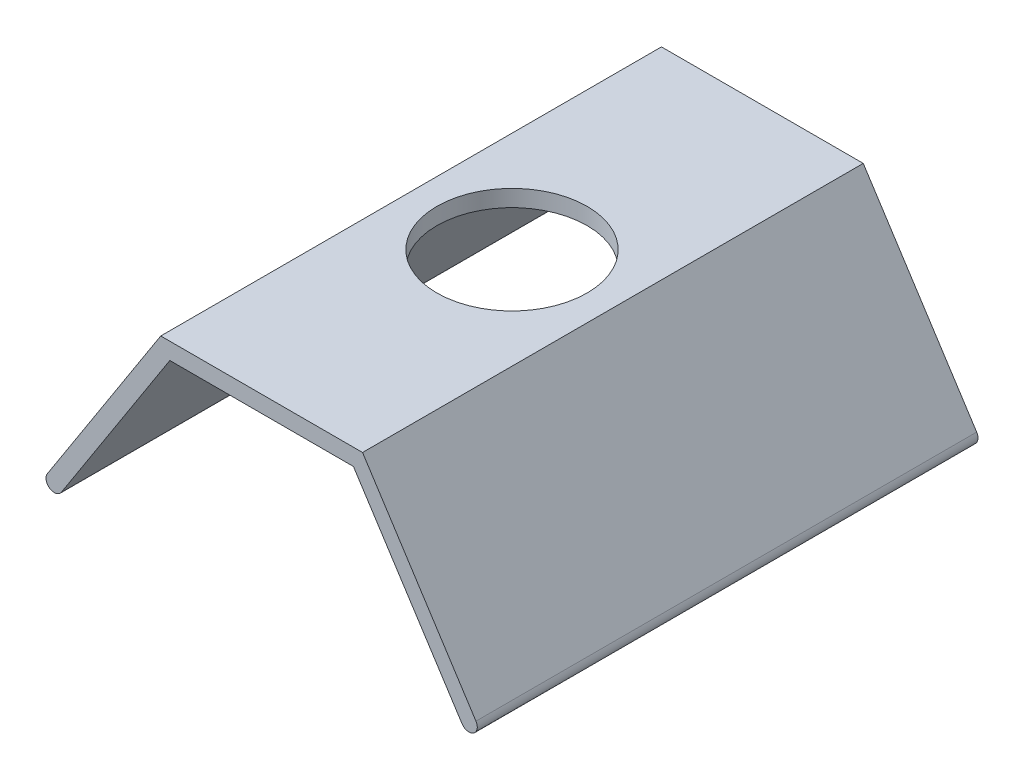
SolidWorks part; units mm, degrees
ref_plane "Front Plane" through (0, 0, 0) normal (0, 0, 1) x (1, 0, 0)
ref_plane "Top Plane" through (0, 0, 0) normal (0, 1, 0) x (1, 0, 0)
ref_plane "Right Plane" through (0, 0, 0) normal (1, 0, 0) x (0, 0, -1)
sketch "Sketch1" plane through (0, 0, 0) normal (0, 0, 1) x (1, 0, 0)
  line L0 (-2.75, 0) -> (2.75, 0)
  line L1 (2.75, 0) -> (6, -5.0436)
  line L2 (-2.75, 0) -> (-6, -5.0436)
  line L3 (3.0226, 0.5) -> (6.4203, -4.7727)
  line L4 (-3.0226, 0.5) -> (3.0226, 0.5)
  line L5 (-3.0226, 0.5) -> (-6.4203, -4.7727)
  arc A0 (6, -5.0436) -> (6.4203, -4.7727) centre (6.2101, -4.9081) ccw
  arc A1 (-6, -5.0436) -> (-6.4203, -4.7727) centre (-6.2101, -4.9081) cw
  point P4 (0, 0)
  dimension "D1" = 12
  dimension "D2" = 5.5
  dimension "D3" = 6
  dimension "D4" = 0.5
extrude "Boss-Extrude1" add sketch "Sketch1" along normal mid plane 15
hole_wizard "M4 Clearance Hole1" positions "Sketch2" profile "Sketch3" hole size "M4" standard "ISO" end condition through all
sketch "Sketch2" plane through (0, 0.5, 0) normal (0, 1, 0) x (1, 0, 0)
  point P0 (0, 0)
sketch "Sketch3" plane through (0, 0.5, 0) normal (1, 0, 0) x (0, 0, 1)
  line L0 (0, 0) -> (0, 5.6581)
  line L1 (0, 5.6581) -> (2.25, 5.6581)
  line L2 (2.25, 5.6581) -> (2.25, 0)
  line L5 (2.25, 0) -> (0, 0)
  line L11 (0, -6.35) -> (0, 107.95) construction
  dimension "Thru Hole Dia." = 4.5
  dimension "Thru Hole Depth" = 5.6581
